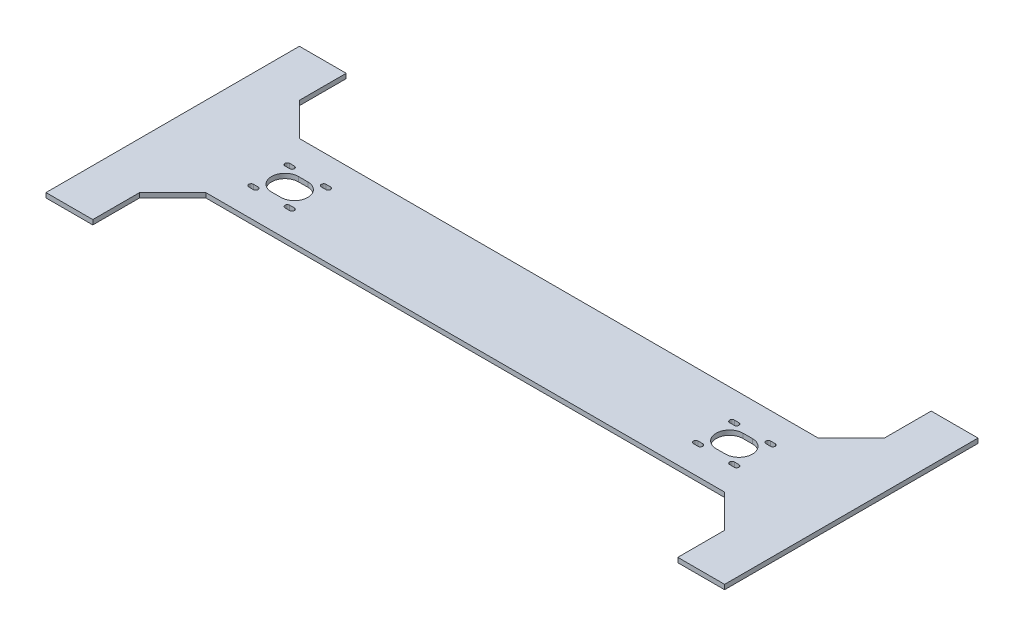
SolidWorks part; units mm, degrees
ref_plane "Front Plane" through (0, 0, 0) normal (0, 0, 1) x (1, 0, 0)
ref_plane "Top Plane" through (0, 0, 0) normal (0, 1, 0) x (1, 0, 0)
ref_plane "Right Plane" through (0, 0, 0) normal (1, 0, 0) x (0, 0, -1)
sketch "Sketch1" plane through (0, 0, 0) normal (0, 1, 0) x (1, 0, 0)
  line L0 (0, 0) -> (-290, 0) construction
  line L1 (-290, 0) -> (-290, 108.2843)
  line L2 (-290, 108.2843) -> (-250, 108.2843)
  line L3 (-250, 108.2843) -> (-250, 68.2843)
  line L4 (-250, 68.2843) -> (-221.7157, 40)
  line L5 (-221.7157, 40) -> (0, 40)
  line L6 (0, 40) -> (0, 0)
  line L7 (-290, 0) -> (0, 0)
  line L8 (-194, 0) -> (-186, 0) construction
  line L9 (-194, 11.5) -> (-186, 11.5)
  line L10 (-207.4998, 15.4998) -> (-203.4998, 15.4998) construction
  line L11 (-190, 0) -> (-225.6507, 35.6507) construction
  line L12 (-207.4998, 17.4998) -> (-203.4998, 17.4998)
  line L13 (-207.4998, 13.4998) -> (-203.4998, 13.4998)
  line L14 (-190, 11.5) -> (-190, 25.0205) construction
  line L15 (-172.5002, 15.4998) -> (-176.5002, 15.4998) construction
  line L16 (-172.5002, 17.4998) -> (-176.5002, 17.4998)
  line L17 (-172.5002, 13.4998) -> (-176.5002, 13.4998)
  arc A0 (-194, 11.5) -> (-205.5, 0) centre (-194, 0) ccw
  arc A1 (-174.5, 0) -> (-186, 11.5) centre (-186, 0) ccw
  arc A2 (-207.4998, 17.4998) -> (-207.4998, 13.4998) centre (-207.4998, 15.4998) ccw
  arc A3 (-203.4998, 13.4998) -> (-203.4998, 17.4998) centre (-203.4998, 15.4998) ccw
  arc A4 (-172.5002, 17.4998) -> (-172.5002, 13.4998) centre (-172.5002, 15.4998) cw
  arc A5 (-176.5002, 13.4998) -> (-176.5002, 17.4998) centre (-176.5002, 15.4998) cw
  point P10 (-190, 0)
  point P19 (-205.4998, 15.4998)
  point P28 (-174.5002, 15.4998)
  dimension "D9" = 11.5
  dimension "D11" = 2
  dimension "D1" = 290
  dimension "D2" = 40
  dimension "D3" = 40
  dimension "D4" = 40
  dimension "D5" = 40
  dimension "D6" = 135
  dimension "D7" = 100
  dimension "D8" = 4
  dimension "D10" = 21.92
  dimension "D12" = 4
extrude "Boss-Extrude1" add sketch "Sketch1" along normal blind 4 contours A1 L7 L6 L5 L4 L3 L2 L1 A0 L9
mirror "Mirror1" about plane through (0, 4, 0) normal (0, 0, -1) of "Boss-Extrude1"
mirror "Mirror5" about plane through (0, 4, 0) normal (1, 0, 0) of "Boss-Extrude1"
mirror "Mirror6" about plane through (0, 4, 0) normal (0, 0, 1) of "Mirror5"
